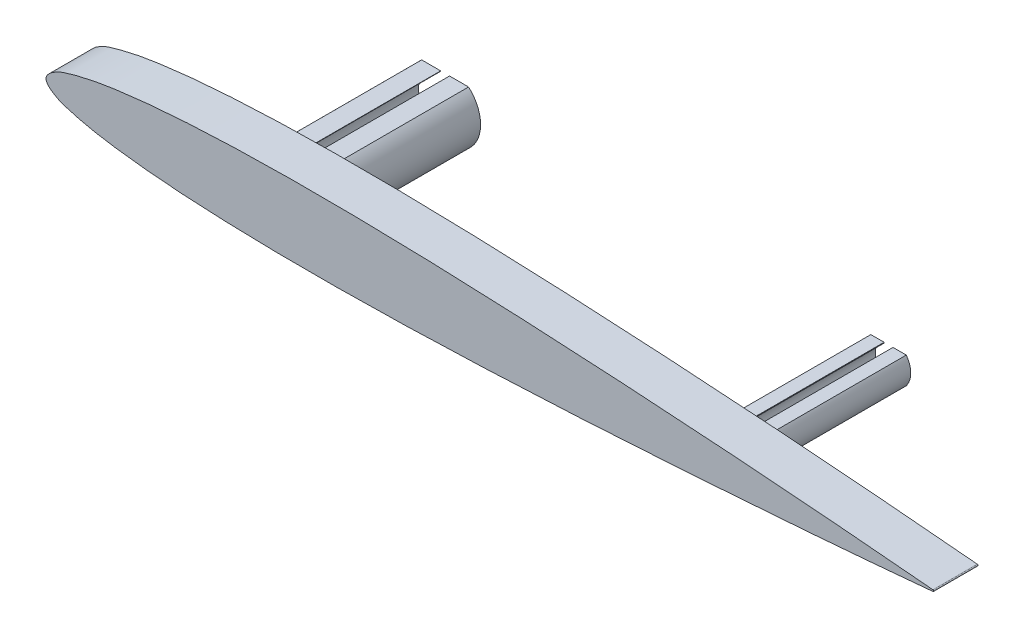
SolidWorks part; units mm, degrees
material "ABS generico"
ref_plane "Piano frontale" through (0, 0, 0) normal (0, 0, 1) x (1, 0, 0)
ref_plane "Piano superiore" through (0, 0, 0) normal (0, 1, 0) x (1, 0, 0)
ref_plane "Piano destro" through (0, 0, 0) normal (1, 0, 0) x (0, 0, -1)
curve "Curva1"
  spline degree 3 poles (100, 0.084, 0) (98.3335, 0.2367, 0) (95.0012, 0.5422, 0) (88.3356, 1.1109, 0) (80.0033, 1.7636, 0) (70.003, 2.4579, 0) (60.0031, 3.0617, 0) (50.003, 3.5521, 0) (40.0026, 3.9029, 0) (31.667, 4.0253, 0) (24.9992, 3.9769, 0) (19.9978, 3.845, 0) (14.9934, 3.5925, 0) (10.8272, 3.2377, 0) (7.4891, 2.814, 0) (4.9936, 2.4037, 0) (2.8496, 1.8679, 0) (1.1654, 1.321, 0) (-0.6646, 0, 0) (1.1654, -1.321, 0) (2.8496, -1.8679, 0) (4.9936, -2.4037, 0) (7.4891, -2.814, 0) (10.8272, -3.2377, 0) (14.9934, -3.5925, 0) (19.9978, -3.845, 0) (24.9992, -3.9769, 0) (31.667, -4.0253, 0) (40.0026, -3.9029, 0) (50.003, -3.5521, 0) (60.0031, -3.0617, 0) (70.003, -2.4579, 0) (80.0033, -1.7636, 0) (88.3356, -1.1109, 0) (95.0012, -0.5422, 0) (98.3335, -0.2367, 0) (100, -0.084, 0) knots 0 0 0 0 0.024876 0.049742 0.099443 0.149112 0.198751 0.248359 0.297937 0.347491 0.372267 0.397051 0.421859 0.446731 0.45922 0.471791 0.48456 0.491195 0.5 0.508805 0.51544 0.528209 0.54078 0.553269 0.578141 0.602949 0.627733 0.652509 0.702063 0.751641 0.801249 0.850888 0.900557 0.950258 0.975124 1 1 1 1
sketch "Schizzo1" plane through (0, 0, 0) normal (0, 0, 1) x (1, 0, 0)
  arc A0 (100, 0.084) -> (100, -0.084) centre (100, 0) cw
  spline S0 degree 3 poles (774.5938, 2905.893) (370.1816, -60.6448) (232.5901, -11.1972) (88.3356, 1.1109) (80.0033, 1.7636) (70.003, 2.4579) (60.0031, 3.0617) (50.003, 3.5521) (40.0026, 3.9029) (31.667, 4.0253) (24.9992, 3.9769) (19.9978, 3.845) (14.9934, 3.5925) (10.8272, 3.2377) (7.4891, 2.814) (4.9936, 2.4037) (2.8496, 1.8679) (1.1654, 1.321) (-0.6646, 0) (1.1654, -1.321) (2.8496, -1.8679) (4.9936, -2.4037) (7.4891, -2.814) (10.8272, -3.2377) (14.9934, -3.5925) (19.9978, -3.845) (24.9992, -3.9769) (31.667, -4.0253) (40.0026, -3.9029) (50.003, -3.5521) (60.0031, -3.0617) (70.003, -2.4579) (80.0033, -1.7636) (88.3356, -1.1109) (232.5893, 11.1971) (370.1799, 60.6442) (774.5865, -2905.8392) knots -2.052665 -2.052665 -2.052665 -2.052665 0.024876 0.049742 0.099443 0.149112 0.198751 0.248359 0.297937 0.347491 0.372267 0.397051 0.421859 0.446731 0.45922 0.471791 0.48456 0.491195 0.5 0.508805 0.51544 0.528209 0.54078 0.553269 0.578141 0.602949 0.627733 0.652509 0.702063 0.751641 0.801249 0.850888 0.900557 0.950258 0.975124 3.052652 3.052652 3.052652 3.052652 only from (100, 0.084) to (100, -0.084) construction
  spline S1 degree 3 poles (100, 0.084) (98.3335, 0.2367) (95.0012, 0.5422) (88.3356, 1.1109) (80.0033, 1.7636) (70.003, 2.4579) (60.0031, 3.0617) (50.003, 3.5521) (40.0026, 3.9029) (31.667, 4.0253) (24.9992, 3.9769) (19.9978, 3.845) (14.9934, 3.5925) (10.8272, 3.2377) (7.4891, 2.814) (4.9936, 2.4037) (2.8496, 1.8679) (1.1654, 1.321) (-0.6646, 0) (1.1654, -1.321) (2.8496, -1.8679) (4.9936, -2.4037) (7.4891, -2.814) (10.8272, -3.2377) (14.9934, -3.5925) (19.9978, -3.845) (24.9992, -3.9769) (31.667, -4.0253) (40.0026, -3.9029) (50.003, -3.5521) (60.0031, -3.0617) (70.003, -2.4579) (80.0033, -1.7636) (88.3356, -1.1109) (95.0012, -0.5422) (98.3335, -0.2367) (100, -0.084) knots 0 0 0 0 0.024876 0.049742 0.099443 0.149112 0.198751 0.248359 0.297937 0.347491 0.372267 0.397051 0.421859 0.446731 0.45922 0.471791 0.48456 0.491195 0.5 0.508805 0.51544 0.528209 0.54078 0.553269 0.578141 0.602949 0.627733 0.652509 0.702063 0.751641 0.801249 0.850888 0.900557 0.950258 0.975124 1 1 1 1
extrude "CorpoCentina" add sketch "Schizzo1" along normal blind 5
sketch "Schizzo2" plane through (0, 0, 0) normal (0, 0, 1) x (1, 0, 0)
  line L0 (25.5, -3) -> (24.5, 3) construction
  line L1 (22.3542, -3) -> (24.5, -3)
  line L3 (22.3542, 3) -> (24.5, 3)
  line L6 (24.5, -3) -> (24.5, -2.958)
  line L8 (25.5, -3) -> (25.5, -2.958)
  line L9 (25.5, 3) -> (24.5, -3) construction
  line L10 (25.5, -3) -> (27.6458, -3)
  line L11 (24.5, 2.958) -> (24.5, 3)
  line L12 (25.5, 2.958) -> (25.5, 3)
  line L13 (25.5, 3) -> (27.6458, 3)
  arc A0 (25.5, -2.958) -> (25.5, 2.958) centre (25, 0) ccw
  arc A1 (27.6458, -3) -> (27.6458, 3) centre (25, 0) ccw
  arc A2 (22.3542, 3) -> (22.3542, -3) centre (25, 0) ccw
  arc A3 (24.5, 2.958) -> (24.5, -2.958) centre (25, 0) ccw
  dimension "D1" = 6
  dimension "D3" = 8
  dimension "D2" = 25
  dimension "D4" = 1
sketch "Schizzo3" plane through (0, 0, 0) normal (0, 0, -1) x (-1, 0, 0)
  line L0 (-77, 1.5) -> (-75.5, 1.5)
  line L1 (-77, -1.5) -> (-75.5, -1.5)
  line L2 (-77, 1.5) -> (-77, -1.5) construction
  line L3 (-73, 1.5) -> (-73, -1.5) construction
  line L4 (-74.5, 1.5) -> (-73, 1.5)
  line L6 (-75.5, 1.5) -> (-75.5, 1.4142)
  line L8 (-74.5, 1.5) -> (-74.5, 1.4142)
  line L9 (-75.5, -1.4142) -> (-75.5, -1.5)
  line L10 (-74.5, -1.4142) -> (-74.5, -1.5)
  line L11 (-74.5, -1.5) -> (-73, -1.5)
  arc A0 (-75.5, 1.4142) -> (-75.5, -1.4142) centre (-75, 0) ccw
  arc A1 (-77, 1.5) -> (-77, -1.5) centre (-75, 0) ccw
  arc A2 (-73, -1.5) -> (-73, 1.5) centre (-75, 0) ccw
  arc A3 (-74.5, -1.4142) -> (-74.5, 1.4142) centre (-75, 0) ccw
  dimension "D1" = 3
  dimension "D2" = 5
  dimension "D3" = 25
  dimension "D4" = 1
  dimension "D5" = 0.0858
extrude "AggancioPernoRuddevator" add sketch "Schizzo3" along normal blind 15
extrude "AggancioLongherone" add sketch "Schizzo2" against normal blind 15
